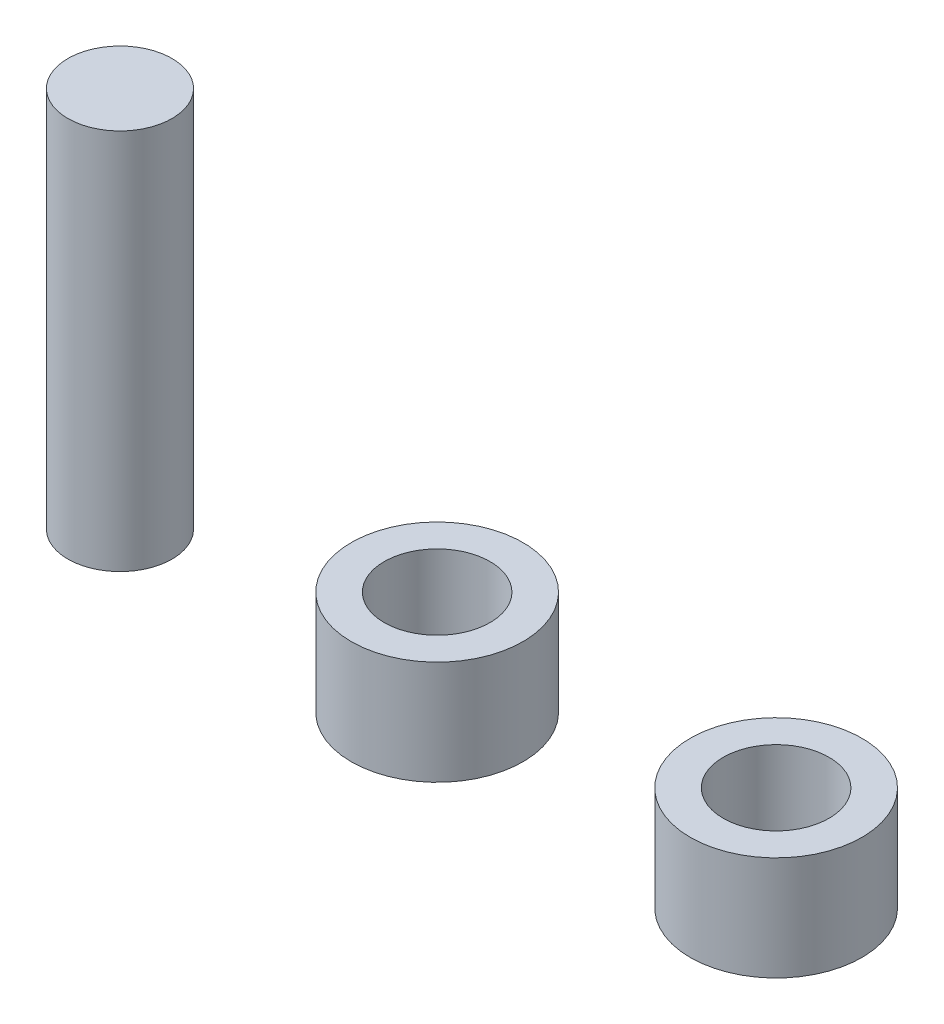
SolidWorks part; units mm, degrees
ref_plane "Front Plane" through (0, 0, 0) normal (0, 0, 1) x (1, 0, 0)
ref_plane "Top Plane" through (0, 0, 0) normal (0, 1, 0) x (1, 0, 0)
ref_plane "Right Plane" through (0, 0, 0) normal (1, 0, 0) x (0, 0, -1)
sketch "Sketch1" plane through (0, 0, 0) normal (0, 1, 0) x (1, 0, 0)
  line L0 (-9.6635, 0) -> (10.2555, 0) construction
  circle A0 centre (0.1146, 0) radius 2.475
  circle A1 centre (0.1146, 0) radius 1.525
  dimension "D1" = 4.95
  dimension "D2" = 3.05
extrude "Boss-Extrude1" add sketch "Sketch1" along normal blind 3
sketch "Sketch2" plane through (0, 0, 0) normal (0, 1, 0) x (1, 0, 0)
  line L0 (-13.1071, 0) -> (16.2343, 0) construction
  circle A0 centre (-9.0273, 0) radius 1.5
  dimension "D1" = 3
extrude "Boss-Extrude2" add sketch "Sketch2" along normal blind 11 separate body contours A0
ref_plane "Plane1" through (5, 0, 0) normal (1, 0, 0) x (0, 0, -1)
mirror "Mirror1" about plane through (5, 0, 0) normal (1, 0, 0) of bodies 101
